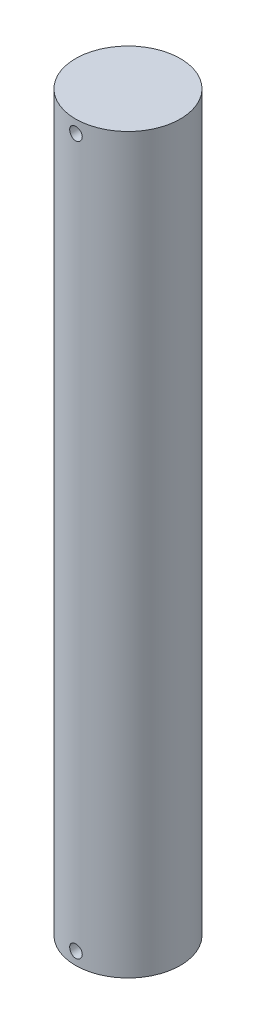
SolidWorks part; units mm, degrees
ref_plane "Front Plane" through (0, 0, 0) normal (0, 0, 1) x (1, 0, 0)
ref_plane "Top Plane" through (0, 0, 0) normal (0, 1, 0) x (1, 0, 0)
ref_plane "Right Plane" through (0, 0, 0) normal (1, 0, 0) x (0, 0, -1)
sketch "Sketch1" plane through (0, 0, 0) normal (0, 1, 0) x (1, 0, 0)
  circle A0 centre (0, 0) radius 250
  dimension "D1" = 500
extrude "Boss-Extrude1" add sketch "Sketch1" along normal blind 3500
sketch "Sketch2" plane through (0, 0, 0) normal (0, 0, 1) x (1, 0, 0)
  line L0 (250, 3500) -> (-250, 3500) construction
  line L1 (-250, 0) -> (250, 0) construction
  circle A0 centre (0, 3440) radius 30
  circle A1 centre (0, 60) radius 30
  dimension "D1" = 60
  dimension "D2" = 60
  dimension "D3" = 60
extrude "Cut-Extrude1" cut sketch "Sketch2" against normal mid plane 3000
